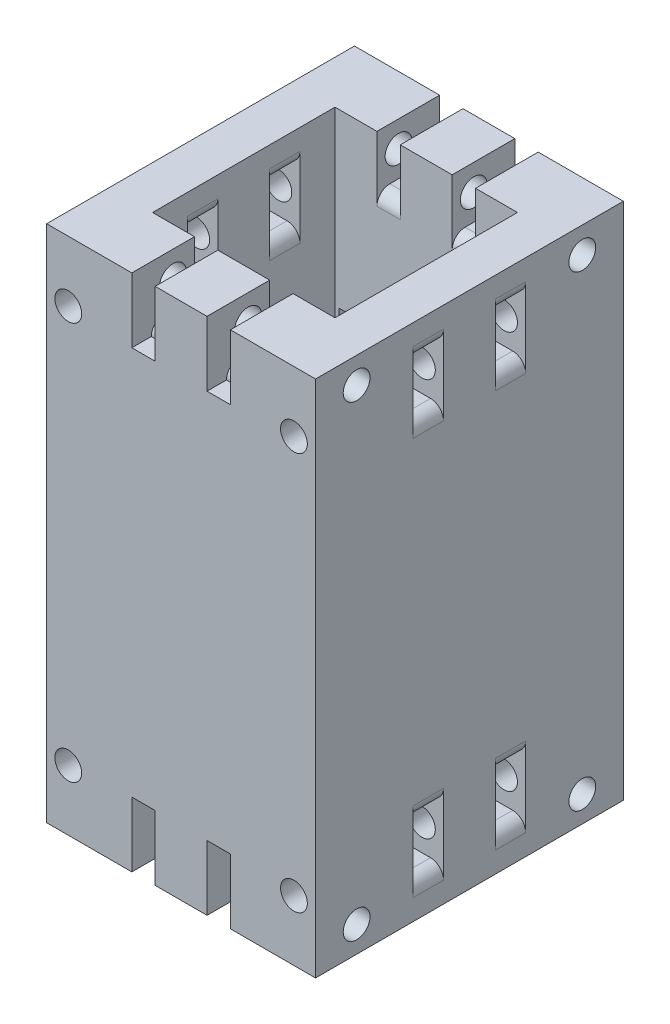
SolidWorks part; units mm, degrees
material "C (石墨)"
ref_plane "前视基准面" through (0, 0, 0) normal (0, 0, 1) x (1, 0, 0)
ref_plane "上视基准面" through (0, 0, 0) normal (0, 1, 0) x (1, 0, 0)
ref_plane "右视基准面" through (0, 0, 0) normal (1, 0, 0) x (0, 0, -1)
other "Configuration Table"
sketch "草图1" plane through (0, 0, 0) normal (0, 1, 0) x (1, 0, 0)
  line L0 (-5, -5) -> (26.1, -5)
  line L1 (0, 0) -> (21.1, 0)
  line L2 (0, 0) -> (0, 21.1)
  line L3 (0, 21.1) -> (21.1, 21.1)
  line L4 (21.1, 0) -> (21.1, 21.1)
  line L5 (26.1, -5) -> (26.1, 26.1)
  line L6 (-5, 26.1) -> (26.1, 26.1)
  line L7 (-5, -5) -> (-5, 26.1)
  dimension "D1" = 21.1
  dimension "D2" = 21.1
  dimension "D3" = 5
extrude "凸台-拉伸1" add sketch "草图1" along normal blind 60
sketch "草图2" plane through (-5, 0, 0) normal (-1, 0, 0) x (0, 0, 1)
  line L0 (-26.1, 60) -> (-26.1, 0) construction
  line L1 (-21.1, 60) -> (-21.1, 0) construction
  line L2 (-26.1, 60) -> (-26.1, 0) construction
  line L3 (-21.1, 60) -> (-21.1, 0) construction
  line L4 (-23.6, 60) -> (-23.6, 0) construction
  line L5 (-26.1, 60) -> (5, 60) construction
  line L6 (-26.1, 0) -> (5, 0) construction
  line L7 (-10.55, 60) -> (-10.55, 0) construction
  circle A0 centre (-23.6, 57) radius 1.55
  circle A1 centre (-23.6, 3) radius 1.55
  circle A2 centre (2.5, 3) radius 1.55
  circle A3 centre (2.5, 57) radius 1.55
  dimension "D4" = 3.1
  dimension "D1" = 2.5
  dimension "D2" = 3
  dimension "D3" = 3
extrude "切除-拉伸1" cut sketch "草图2" against normal through all
sketch "草图3" plane through (0, 0, -21.1) normal (0, 0, 1) x (1, 0, 0)
  line L0 (10.55, 60) -> (10.55, 0) construction
  line L1 (26.1, 30) -> (-5, 30) construction
  line L2 (4.85, 60) -> (7.55, 60)
  line L3 (4.85, 60) -> (4.85, 54)
  line L4 (0, 0) -> (21.1, 0)
  line L5 (21.1, 0) -> (21.1, 60)
  line L6 (21.1, 60) -> (0, 60)
  line L7 (0, 60) -> (0, 0)
  line L8 (0, 0) -> (21.1, 0) construction
  line L9 (21.1, 0) -> (21.1, 60) construction
  line L10 (21.1, 60) -> (0, 60) construction
  line L11 (0, 60) -> (0, 0) construction
  line L12 (4.85, 54) -> (7.55, 54)
  line L13 (7.55, 60) -> (7.55, 54)
  line L14 (13.55, 60) -> (16.25, 60)
  line L15 (13.55, 60) -> (13.55, 54)
  line L16 (13.55, 54) -> (16.25, 54)
  line L17 (16.25, 60) -> (16.25, 54)
  line L18 (26.1, 60) -> (26.1, 0) construction
  line L19 (-5, 60) -> (-5, 0) construction
  line L20 (16.25, 0) -> (16.25, 6)
  line L21 (13.55, 6) -> (16.25, 6)
  line L22 (13.55, 0) -> (13.55, 6)
  line L23 (13.55, 0) -> (16.25, 0)
  line L24 (7.55, 0) -> (7.55, 6)
  line L25 (4.85, 6) -> (7.55, 6)
  line L26 (4.85, 0) -> (4.85, 6)
  line L27 (4.85, 0) -> (7.55, 0)
  dimension "D2" = 6
  dimension "D3" = 2.7
  dimension "D4" = 3
  dimension "D1" = 0
extrude "切除-拉伸2" cut sketch "草图3" against normal through all and the other way through all
sketch "草图4" plane through (0, 0, -26.1) normal (0, 0, -1) x (-1, 0, 0)
  line L0 (-23.6, 60) -> (-23.6, 0) construction
  line L1 (-26.1, 60) -> (-16.25, 60) construction
  line L2 (-26.1, 0) -> (-16.25, 0) construction
  line L3 (-26.1, 60) -> (-26.1, 0) construction
  line L4 (-26.1, 30) -> (5, 30) construction
  line L5 (5, 60) -> (5, 0) construction
  line L6 (-10.55, 60) -> (-10.55, 0) construction
  line L7 (-13.55, 60) -> (-7.55, 60) construction
  line L8 (-13.55, 0) -> (-7.55, 0) construction
  circle A0 centre (-23.6, 53) radius 1.55
  circle A1 centre (2.5, 53) radius 1.55
  circle A2 centre (2.5, 7) radius 1.55
  circle A3 centre (-23.6, 7) radius 1.55
  dimension "D2" = 3.1
  dimension "D1" = 2.5
  dimension "D3" = 7
extrude "切除-拉伸3" cut sketch "草图4" against normal through all
sketch "草图5" plane through (21.1, 0, 0) normal (-1, 0, 0) x (0, 0, 1)
  line L0 (-10.55, 60) -> (-10.55, 0) construction
  line L1 (-26.1, 60) -> (5, 60) construction
  line L2 (-26.1, 0) -> (5, 0) construction
  line L3 (-26.1, 53) -> (5, 53) construction
  line L4 (-26.1, 60) -> (-26.1, 0) construction
  line L5 (5, 60) -> (5, 0) construction
  line L6 (5, 30) -> (-26.1, 30) construction
  line L7 (-17.05, 56.1) -> (-13.55, 56.1)
  line L8 (-17.05, 56.1) -> (-17.05, 49.9)
  line L9 (-17.05, 49.9) -> (-13.55, 49.9)
  line L10 (-13.55, 56.1) -> (-13.55, 49.9)
  line L11 (-7.55, 56.1) -> (-4.05, 56.1)
  line L12 (-7.55, 56.1) -> (-7.55, 49.9)
  line L13 (-7.55, 49.9) -> (-4.05, 49.9)
  line L14 (-4.05, 56.1) -> (-4.05, 49.9)
  line L15 (-4.05, 3.9) -> (-4.05, 10.1)
  line L16 (-7.55, 10.1) -> (-4.05, 10.1)
  line L17 (-7.55, 3.9) -> (-7.55, 10.1)
  line L18 (-7.55, 3.9) -> (-4.05, 3.9)
  line L19 (-13.55, 3.9) -> (-13.55, 10.1)
  line L20 (-17.05, 10.1) -> (-13.55, 10.1)
  line L21 (-17.05, 3.9) -> (-17.05, 10.1)
  line L22 (-17.05, 3.9) -> (-13.55, 3.9)
  dimension "D1" = 7
  dimension "D2" = 3
  dimension "D3" = 3.5
  dimension "D4" = 6.2
  dimension "D5" = 6.2
extrude "切除-拉伸4" cut sketch "草图5" against normal through all and the other way through all
ref_plane "基准面1" through (0, 30, 0) normal (0, 1, 0) x (1, 0, 0)
fillet "圆角1" radius 1.5 48 edges at (14.9, 6, 0) (14.9, 6, 5) (6.2, 6, 0) (6.2, 6, 5) (6.2, 6, -21.1) (6.2, 6, -26.1) (14.9, 6, -21.1) (14.9, 6, -26.1) (21.1, 10.1, -15.3) (21.1, 10.1, -5.8) (26.1, 10.1, -15.3) (26.1, 10.1, -5.8) (26.1, 3.9, -15.3) (21.1, 3.9, -15.3) (26.1, 3.9, -5.8) (21.1, 3.9, -5.8) (0, 10.1, -5.8) (0, 10.1, -15.3) (-5, 10.1, -5.8) (-5, 10.1, -15.3) (-5, 3.9, -5.8) (0, 3.9, -5.8) (0, 3.9, -15.3) (-5, 3.9, -15.3) (21.1, 56.1, -5.8) (26.1, 56.1, -5.8) (0, 56.1, -5.8) (0, 56.1, -15.3) (-5, 56.1, -5.8) (-5, 56.1, -15.3) (0, 49.9, -5.8) (0, 49.9, -15.3) (-5, 49.9, -5.8) (-5, 49.9, -15.3) (6.2, 54, -21.1) (14.9, 54, -21.1) (6.2, 54, -26.1) (14.9, 54, -26.1) (26.1, 56.1, -15.3) (21.1, 56.1, -15.3) (21.1, 49.9, -15.3) (21.1, 49.9, -5.8) (26.1, 49.9, -5.8) (14.9, 54, 5) (6.2, 54, 0) (14.9, 54, 0) (6.2, 54, 5) (26.1, 49.9, -15.3)
sketch "草图6" plane through (0, 0, 5) normal (0, 0, 1) x (1, 0, 0)
  line L0 (5.4175, 30) -> (-5.4175, 30) construction
  line L1 (0.45, 40.1) -> (20.65, 40.1)
  line L2 (0.45, 40.1) -> (0.45, 19.9)
  line L3 (0.45, 19.9) -> (20.65, 19.9)
  line L4 (20.65, 40.1) -> (20.65, 19.9)
  line L5 (0.45, 40.1) -> (20.65, 19.9) construction
  line L6 (0.45, 19.9) -> (20.65, 40.1) construction
  line L7 (10.55, 30) -> (26.2189, 30) construction
  line L8 (26.2189, 30) -> (24.6313, 30)
  line L9 (10.55, 30) -> (10.55, 60) construction
  line L10 (7.55, 60) -> (13.55, 60) construction
  point P0 (10.55, 30)
  dimension "D1" = 20.2
  dimension "D2" = 20.2
extrude "切除-拉伸5" cut sketch "草图6" against normal through all contours L4 L1 L2 L3
sketch "草图7" plane through (0, 0, 5) normal (0, 0, 1) x (1, 0, 0)
  line L20 (13.55, 0) -> (13.55, 7.5)
  line L21 (13.55, 7.5) -> (16.25, 7.5)
  line L22 (16.25, 7.5) -> (16.25, 0)
  line L23 (16.25, 0) -> (26.1, 0)
  line L24 (26.1, 0) -> (26.1, 60)
  line L25 (26.1, 60) -> (16.25, 60)
  line L26 (16.25, 60) -> (16.25, 52.5)
  line L27 (16.25, 52.5) -> (13.55, 52.5)
  line L28 (13.55, 52.5) -> (13.55, 60)
  line L29 (13.55, 60) -> (7.55, 60)
  line L30 (7.55, 60) -> (7.55, 52.5)
  line L31 (7.55, 52.5) -> (4.85, 52.5)
  line L32 (4.85, 52.5) -> (4.85, 60)
  line L33 (4.85, 60) -> (-5, 60)
  line L34 (-5, 60) -> (-5, 0)
  line L35 (-5, 0) -> (4.85, 0)
  line L36 (4.85, 0) -> (4.85, 7.5)
  line L37 (4.85, 7.5) -> (7.55, 7.5)
  line L38 (7.55, 7.5) -> (7.55, 0)
  line L39 (7.55, 0) -> (13.55, 0)
  line L40 (13.55, 0) -> (13.55, 7.5)
  line L41 (13.55, 7.5) -> (16.25, 7.5)
  line L42 (16.25, 7.5) -> (16.25, 0)
  line L43 (16.25, 0) -> (26.1, 0)
  line L44 (26.1, 0) -> (26.1, 60)
  line L45 (26.1, 60) -> (16.25, 60)
  line L46 (16.25, 60) -> (16.25, 52.5)
  line L47 (16.25, 52.5) -> (13.55, 52.5)
  line L48 (13.55, 52.5) -> (13.55, 60)
  line L49 (13.55, 60) -> (7.55, 60)
  line L50 (7.55, 60) -> (7.55, 52.5)
  line L51 (7.55, 52.5) -> (4.85, 52.5)
  line L52 (4.85, 52.5) -> (4.85, 60)
  line L53 (4.85, 60) -> (-5, 60)
  line L54 (-5, 60) -> (-5, 0)
  line L55 (-5, 0) -> (4.85, 0)
  line L56 (4.85, 0) -> (4.85, 7.5)
  line L57 (4.85, 7.5) -> (7.55, 7.5)
  line L58 (7.55, 7.5) -> (7.55, 0)
  line L59 (7.55, 0) -> (13.55, 0)
  circle A0 centre (23.6, 7) radius 1.55 construction
  circle A1 centre (23.6, 53) radius 1.55 construction
  circle A2 centre (-2.5, 53) radius 1.55 construction
  circle A3 centre (-2.5, 7) radius 1.55 construction
  circle A4 centre (23.6, 7) radius 1.55
  circle A5 centre (23.6, 53) radius 1.55
  circle A6 centre (-2.5, 53) radius 1.55
  circle A7 centre (-2.5, 7) radius 1.55
  dimension "D1" = 0
sketch "草图8" plane through (0, 0, -26.1) normal (0, 0, -1) x (-1, 0, 0)
  line L20 (-7.55, 7.5) -> (-4.85, 7.5)
  line L21 (-4.85, 7.5) -> (-4.85, 0)
  line L22 (-4.85, 0) -> (5, 0)
  line L23 (5, 0) -> (5, 60)
  line L24 (5, 60) -> (-4.85, 60)
  line L25 (-4.85, 60) -> (-4.85, 52.5)
  line L26 (-4.85, 52.5) -> (-7.55, 52.5)
  line L27 (-7.55, 52.5) -> (-7.55, 60)
  line L28 (-7.55, 60) -> (-13.55, 60)
  line L29 (-13.55, 60) -> (-13.55, 52.5)
  line L30 (-13.55, 52.5) -> (-16.25, 52.5)
  line L31 (-16.25, 52.5) -> (-16.25, 60)
  line L32 (-16.25, 60) -> (-26.1, 60)
  line L33 (-26.1, 60) -> (-26.1, 0)
  line L34 (-26.1, 0) -> (-16.25, 0)
  line L35 (-16.25, 0) -> (-16.25, 7.5)
  line L36 (-16.25, 7.5) -> (-13.55, 7.5)
  line L37 (-13.55, 7.5) -> (-13.55, 0)
  line L38 (-13.55, 0) -> (-7.55, 0)
  line L39 (-7.55, 0) -> (-7.55, 7.5)
  line L40 (-7.55, 7.5) -> (-4.85, 7.5)
  line L41 (-4.85, 7.5) -> (-4.85, 0)
  line L42 (-4.85, 0) -> (5, 0)
  line L43 (5, 0) -> (5, 60)
  line L44 (5, 60) -> (-4.85, 60)
  line L45 (-4.85, 60) -> (-4.85, 52.5)
  line L46 (-4.85, 52.5) -> (-7.55, 52.5)
  line L47 (-7.55, 52.5) -> (-7.55, 60)
  line L48 (-7.55, 60) -> (-13.55, 60)
  line L49 (-13.55, 60) -> (-13.55, 52.5)
  line L50 (-13.55, 52.5) -> (-16.25, 52.5)
  line L51 (-16.25, 52.5) -> (-16.25, 60)
  line L52 (-16.25, 60) -> (-26.1, 60)
  line L53 (-26.1, 60) -> (-26.1, 0)
  line L54 (-26.1, 0) -> (-16.25, 0)
  line L55 (-16.25, 0) -> (-16.25, 7.5)
  line L56 (-16.25, 7.5) -> (-13.55, 7.5)
  line L57 (-13.55, 7.5) -> (-13.55, 0)
  line L58 (-13.55, 0) -> (-7.55, 0)
  line L59 (-7.55, 0) -> (-7.55, 7.5)
  circle A0 centre (-23.6, 7) radius 1.55 construction
  circle A1 centre (2.5, 7) radius 1.55 construction
  circle A2 centre (2.5, 53) radius 1.55 construction
  circle A3 centre (-23.6, 53) radius 1.55 construction
  circle A4 centre (-23.6, 7) radius 1.55
  circle A5 centre (2.5, 7) radius 1.55
  circle A6 centre (2.5, 53) radius 1.55
  circle A7 centre (-23.6, 53) radius 1.55
  dimension "D1" = 0
extrude "凸台-拉伸2" add sketch "草图7" along normal blind 2.25
extrude "凸台-拉伸3" add sketch "草图8" along normal blind 2.25
sketch "草图9" plane through (0, 0, -28.35) normal (0, 0, -1) x (-1, 0, 0)
  line L0 (-21.1, 60) -> (-21.1, 0) construction
  line L1 (-21.1, 60) -> (-21.1, 0) construction
  line L2 (-21.1, 60) -> (-26.1, 60)
  line L3 (-26.1, 60) -> (-26.1, 0)
  line L4 (-26.1, 0) -> (-21.1, 0)
  line L5 (-21.1, 0) -> (-21.1, 60)
